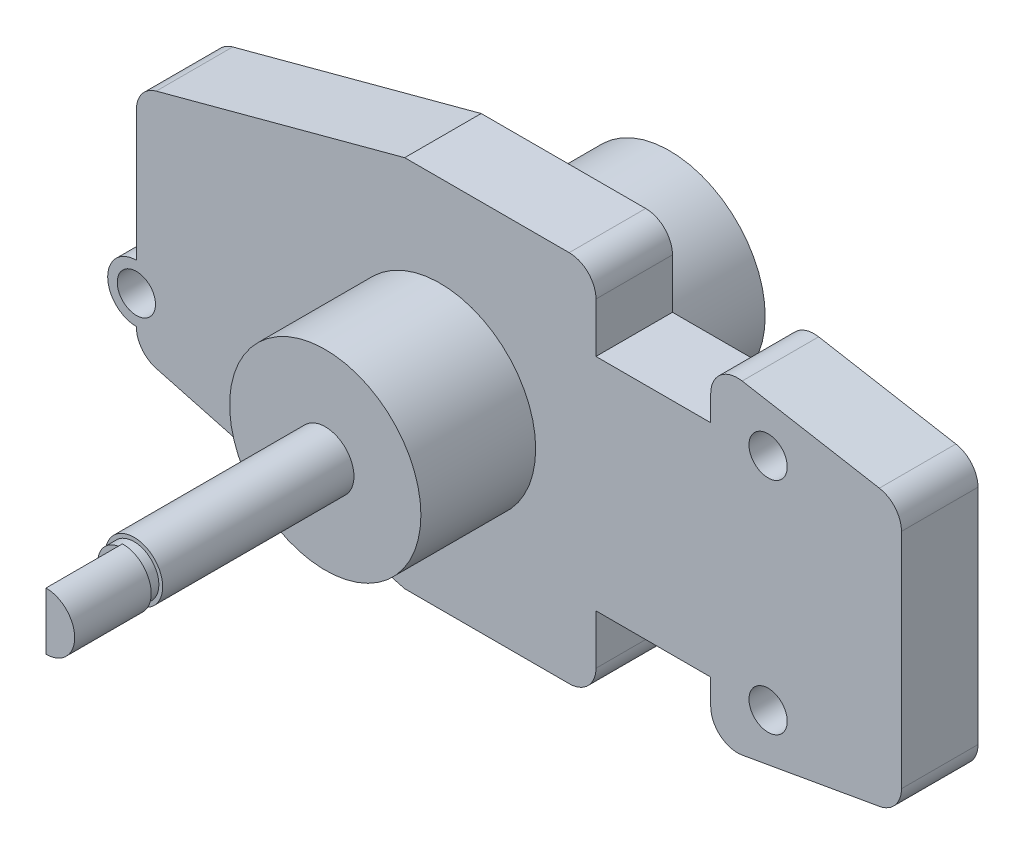
SolidWorks part; units mm, degrees
ref_plane "Front Plane" through (0, 0, 0) normal (0, 0, 1) x (1, 0, 0)
ref_plane "Top Plane" through (0, 0, 0) normal (0, 1, 0) x (1, 0, 0)
ref_plane "Right Plane" through (0, 0, 0) normal (1, 0, 0) x (0, 0, -1)
sketch "Sketch2" plane through (0, 0, 0) normal (0, 0, 1) x (1, 0, 0)
  line L0 (-15.6042, 0) -> (22.5625, 0) construction
  line L1 (-7.9375, -2.4629) -> (-7.9375, 2.4629)
  line L2 (-7.4187, 3.139) -> (-0.924, 4.8793)
  line L3 (-0.924, 4.8793) -> (3.376, 4.8793)
  line L4 (4.076, 4.1793) -> (4.076, 2.8793)
  line L5 (4.076, 2.8793) -> (7.076, 2.8793)
  line L6 (7.076, 2.8793) -> (7.076, 3.545)
  line L7 (7.8975, 4.2344) -> (11.4841, 3.602)
  line L8 (12.0625, 2.9126) -> (12.0625, -2.9126)
  line L9 (12.0625, 0) -> (-7.9375, 0)
  line L10 (7.8975, -4.2344) -> (11.4841, -3.602)
  line L11 (7.076, -2.8793) -> (7.076, -3.545)
  line L12 (4.076, -2.8793) -> (7.076, -2.8793)
  line L13 (4.076, -4.1793) -> (4.076, -2.8793)
  line L14 (-0.924, -4.8793) -> (3.376, -4.8793)
  line L15 (-7.4187, -3.139) -> (-0.924, -4.8793)
  arc A0 (7.8975, -4.2344) -> (7.076, -3.545) centre (7.776, -3.545) cw
  arc A1 (4.076, -4.1793) -> (3.376, -4.8793) centre (3.376, -4.1793) cw
  arc A2 (11.4841, -3.602) -> (12.0625, -2.9126) centre (11.3625, -2.9126) ccw
  arc A3 (11.4841, 3.602) -> (12.0625, 2.9126) centre (11.3625, 2.9126) cw
  arc A4 (7.076, 3.545) -> (7.8975, 4.2344) centre (7.776, 3.545) cw
  arc A5 (3.376, 4.8793) -> (4.076, 4.1793) centre (3.376, 4.1793) cw
  arc A6 (-7.4187, -3.139) -> (-7.9375, -2.4629) centre (-7.2375, -2.4629) cw
  arc A7 (-7.9375, 2.4629) -> (-7.4187, 3.139) centre (-7.2375, 2.4629) cw
  point P21 (7.076, -4.3793)
  point P24 (4.076, -4.8793)
  point P27 (12.0625, -3.5)
  point P30 (12.0625, 3.5)
  point P33 (7.076, 4.3793)
  point P36 (4.076, 4.8793)
  point P39 (-7.9375, -3)
  point P42 (-7.9375, 3)
  dimension "D10" = 0.7
  dimension "D11" = 0.7
  dimension "D1" = 3
  dimension "D2" = 15
  dimension "D3" = 5
  dimension "D4" = 2
  dimension "D5" = 1.5
  dimension "D6" = 3
  dimension "D7" = 3.5
  dimension "D8" = 10
  dimension "D9" = 20
extrude "Boss-Extrude1" add sketch "Sketch2" along normal blind 2 contours L1 L15 L14 L13 L12 L11 L10 L8 L9 | L9 L8 L7 L6 L5 L4 L3 L2 L1
sketch "Sketch3" plane through (0, 0, 2) normal (0, 0, 1) x (1, 0, 0)
  circle A0 centre (8.576, 2.8793) radius 0.5
  circle A1 centre (8.576, -2.8793) radius 0.5
  dimension "D1" = 1
  dimension "D2" = 1
  dimension "D3" = 1.5
  dimension "D4" = 1.5
extrude "Cut-Extrude1" cut sketch "Sketch3" against normal blind 2
sketch "Sketch4" plane through (0, 0, 2) normal (0, 0, 1) x (1, 0, 0)
  line L0 (-7.9375, -2.4629) -> (-7.9375, 2.4629) construction
  circle A0 centre (-7.9375, -1.7) radius 0.75
  dimension "D2" = 1.5
  dimension "D1" = 1.7
extrude "Boss-Extrude2" add sketch "Sketch4" against normal blind 1
sketch "Sketch5" plane through (0, 0, 2) normal (0, 0, 1) x (1, 0, 0)
  circle A0 centre (-7.9375, -1.7) radius 0.5
  dimension "D1" = 1
extrude "Cut-Extrude2" cut sketch "Sketch5" against normal blind 2
sketch "Sketch6" plane through (0, 0, 2) normal (0, 0, 1) x (1, 0, 0)
  circle A0 centre (0, 0) radius 2.5
  dimension "D1" = 5
extrude "Boss-Extrude3" add sketch "Sketch6" along normal blind 3 and the other way blind 6
sketch "Sketch7" plane through (0, 0, 5) normal (0, 0, 1) x (1, 0, 0)
  circle A0 centre (0, 0) radius 0.75
  dimension "D1" = 1.5
extrude "Boss-Extrude4" add sketch "Sketch7" along normal blind 5
sketch "Sketch9" plane through (0, 0, 10) normal (0, 0, 1) x (1, 0, 0)
  circle A0 centre (0, 0) radius 0.65
  dimension "D1" = 1.3
extrude "Boss-Extrude5" add sketch "Sketch9" along normal blind 0.3
sketch "Sketch10" plane through (0, 0, 10.3) normal (0, 0, 1) x (1, 0, 0)
  line L0 (0, 0.75) -> (0, -0.75)
  arc A0 (0, -0.75) -> (0, 0.75) centre (0, 0) ccw
extrude "Boss-Extrude6" add sketch "Sketch10" along normal blind 2
